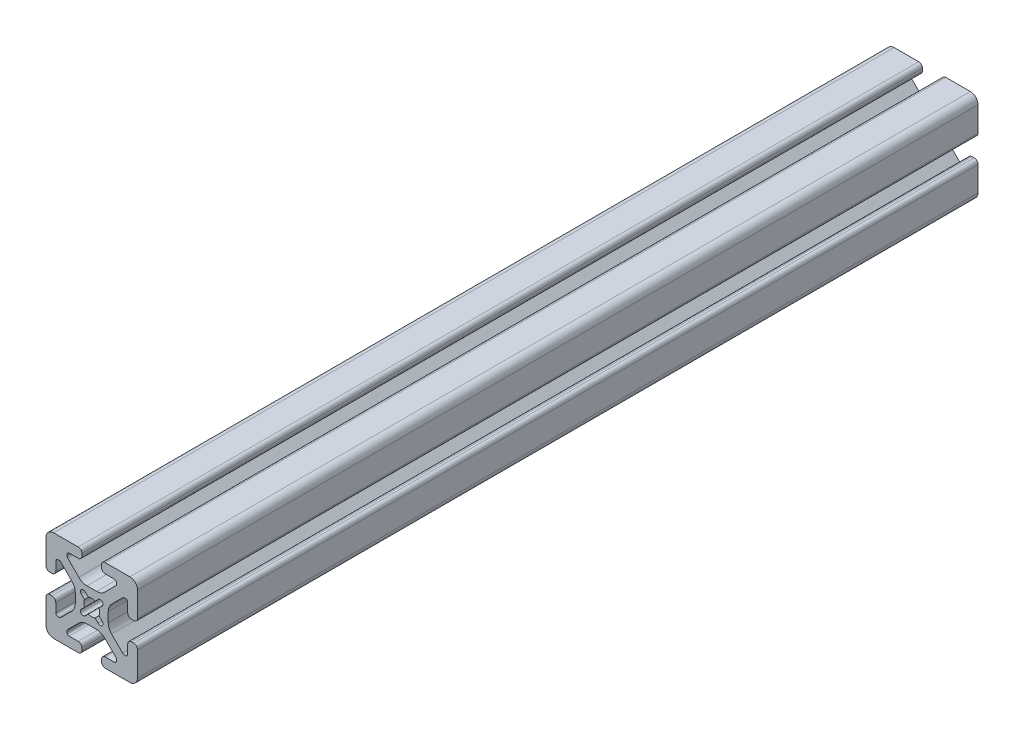
SolidWorks part; units mm, degrees
material "6061-T6 (SS)"
ref_plane "Front Plane" through (0, 0, 0) normal (0, 0, 1) x (1, 0, 0)
ref_plane "Top Plane" through (0, 0, 0) normal (0, 1, 0) x (1, 0, 0)
ref_plane "Right Plane" through (0, 0, 0) normal (1, 0, 0) x (0, 0, -1)
sketch "Sketch1" plane through (0, 0, 0) normal (0, 0, 1) x (1, 0, 0)
  line L0 (4.2456, 2.6398) -> (3.0178, 1.4017)
  line L1 (3.0179, -1.4014) -> (4.3433, -2.7269)
  line L2 (2.7269, -4.3433) -> (1.4014, -3.0179)
  line L3 (-1.4014, -3.0179) -> (-2.7269, -4.3433)
  line L4 (-4.3433, -2.7269) -> (-3.0179, -1.4014)
  line L5 (-3.0179, 1.4014) -> (-4.3433, 2.7269)
  line L6 (-2.7269, 4.3433) -> (-1.4014, 3.0179)
  line L7 (1.4017, 3.0178) -> (2.6398, 4.2456)
  line L8 (14.986, -5.6388) -> (14.986, -9.398)
  line L9 (14.097, -10.287) -> (13.5289, -10.287)
  line L10 (12.9003, -10.0266) -> (8.2608, -5.3872)
  line L11 (6.8697, -2.0285) -> (6.8697, 2.0285)
  line L12 (8.2608, 5.3872) -> (12.9003, 10.0266)
  line L13 (13.5289, 10.287) -> (14.097, 10.287)
  line L14 (14.986, 9.398) -> (14.986, 5.6388)
  line L15 (16.5608, 4.064) -> (17.4752, 4.064)
  line L16 (19.05, 5.6388) -> (19.05, 15.875)
  line L17 (15.875, 19.05) -> (5.6388, 19.05)
  line L18 (4.064, 17.4752) -> (4.064, 16.5608)
  line L19 (5.6388, 14.986) -> (9.398, 14.986)
  line L20 (10.287, 14.097) -> (10.287, 13.5289)
  line L21 (10.0266, 12.9003) -> (5.3872, 8.2608)
  line L22 (2.0285, 6.8697) -> (-2.0285, 6.8697)
  line L23 (-5.3872, 8.2608) -> (-10.0266, 12.9003)
  line L24 (-10.287, 13.5289) -> (-10.287, 14.097)
  line L25 (-9.398, 14.986) -> (-5.6388, 14.986)
  line L26 (-4.064, 16.5608) -> (-4.064, 17.4752)
  line L27 (-5.6388, 19.05) -> (-15.875, 19.05)
  line L28 (-19.05, 15.875) -> (-19.05, 5.6388)
  line L29 (-17.4752, 4.064) -> (-16.5608, 4.064)
  line L30 (-14.986, 5.6388) -> (-14.986, 9.398)
  line L31 (-14.097, 10.287) -> (-13.5289, 10.287)
  line L32 (-12.9003, 10.0266) -> (-8.2608, 5.3872)
  line L33 (-6.8697, 2.0285) -> (-6.8697, -2.0285)
  line L34 (-8.2608, -5.3872) -> (-12.9003, -10.0266)
  line L35 (-13.5289, -10.287) -> (-14.097, -10.287)
  line L36 (-14.986, -9.398) -> (-14.986, -5.6388)
  line L37 (-16.5608, -4.064) -> (-17.4752, -4.064)
  line L38 (-19.05, -5.6388) -> (-19.05, -15.875)
  line L39 (-15.875, -19.05) -> (-5.6388, -19.05)
  line L40 (-4.064, -17.4752) -> (-4.064, -16.5608)
  line L41 (-5.6388, -14.986) -> (-9.398, -14.986)
  line L42 (-10.287, -14.097) -> (-10.287, -13.5289)
  line L43 (-10.0266, -12.9003) -> (-5.3872, -8.2608)
  line L44 (-2.0285, -6.8697) -> (2.0285, -6.8697)
  line L45 (5.3872, -8.2608) -> (10.0266, -12.9003)
  line L46 (10.287, -13.5289) -> (10.287, -14.097)
  line L47 (9.398, -14.986) -> (5.6388, -14.986)
  line L48 (4.064, -16.5608) -> (4.064, -17.4752)
  line L49 (5.6388, -19.05) -> (15.875, -19.05)
  line L50 (19.05, -15.875) -> (19.05, -5.6388)
  line L51 (17.4752, -4.064) -> (16.5608, -4.064)
  arc A0 (4.2456, 2.6398) -> (2.6398, 4.2456) centre (3.5351, 3.5351) ccw
  arc A1 (1.4017, 3.0178) -> (-1.4014, 3.0179) centre (0, 0) ccw
  arc A2 (2.7269, -4.3433) -> (4.3433, -2.7269) centre (3.5351, -3.5351) ccw
  arc A3 (-3.0179, 1.4014) -> (-3.0179, -1.4014) centre (0, 0) ccw
  arc A4 (-4.3433, -2.7269) -> (-2.7269, -4.3433) centre (-3.5351, -3.5351) ccw
  arc A5 (-1.4014, -3.0179) -> (1.4014, -3.0179) centre (0, 0) ccw
  arc A6 (-2.7269, 4.3433) -> (-4.3433, 2.7269) centre (-3.5351, 3.5351) ccw
  arc A8 (16.5608, -4.064) -> (14.986, -5.6388) centre (16.5608, -5.6388) ccw
  arc A9 (14.097, -10.287) -> (14.986, -9.398) centre (14.097, -9.398) ccw
  arc A10 (12.9003, -10.0266) -> (13.5289, -10.287) centre (13.5289, -9.398) ccw
  arc A11 (6.8697, -2.0285) -> (8.2608, -5.3872) centre (11.6195, -2.0285) ccw
  arc A12 (8.2608, 5.3872) -> (6.8697, 2.0285) centre (11.6195, 2.0285) ccw
  arc A13 (13.5289, 10.287) -> (12.9003, 10.0266) centre (13.5289, 9.398) ccw
  arc A14 (14.986, 9.398) -> (14.097, 10.287) centre (14.097, 9.398) ccw
  arc A15 (14.986, 5.6388) -> (16.5608, 4.064) centre (16.5608, 5.6388) ccw
  arc A16 (17.4752, 4.064) -> (19.05, 5.6388) centre (17.4752, 5.6388) ccw
  arc A17 (19.05, 15.875) -> (15.875, 19.05) centre (15.875, 15.875) ccw
  arc A18 (5.6388, 19.05) -> (4.064, 17.4752) centre (5.6388, 17.4752) ccw
  arc A19 (4.064, 16.5608) -> (5.6388, 14.986) centre (5.6388, 16.5608) ccw
  arc A20 (10.287, 14.097) -> (9.398, 14.986) centre (9.398, 14.097) ccw
  arc A21 (10.0266, 12.9003) -> (10.287, 13.5289) centre (9.398, 13.5289) ccw
  arc A22 (2.0285, 6.8697) -> (5.3872, 8.2608) centre (2.0285, 11.6195) ccw
  arc A23 (-5.3872, 8.2608) -> (-2.0285, 6.8697) centre (-2.0285, 11.6195) ccw
  arc A24 (-10.287, 13.5289) -> (-10.0266, 12.9003) centre (-9.398, 13.5289) ccw
  arc A25 (-9.398, 14.986) -> (-10.287, 14.097) centre (-9.398, 14.097) ccw
  arc A26 (-5.6388, 14.986) -> (-4.064, 16.5608) centre (-5.6388, 16.5608) ccw
  arc A27 (-4.064, 17.4752) -> (-5.6388, 19.05) centre (-5.6388, 17.4752) ccw
  arc A28 (-15.875, 19.05) -> (-19.05, 15.875) centre (-15.875, 15.875) ccw
  arc A29 (-19.05, 5.6388) -> (-17.4752, 4.064) centre (-17.4752, 5.6388) ccw
  arc A30 (-16.5608, 4.064) -> (-14.986, 5.6388) centre (-16.5608, 5.6388) ccw
  arc A31 (-14.097, 10.287) -> (-14.986, 9.398) centre (-14.097, 9.398) ccw
  arc A32 (-12.9003, 10.0266) -> (-13.5289, 10.287) centre (-13.5289, 9.398) ccw
  arc A33 (-6.8697, 2.0285) -> (-8.2608, 5.3872) centre (-11.6195, 2.0285) ccw
  arc A34 (-8.2608, -5.3872) -> (-6.8697, -2.0285) centre (-11.6195, -2.0285) ccw
  arc A35 (-13.5289, -10.287) -> (-12.9003, -10.0266) centre (-13.5289, -9.398) ccw
  arc A36 (-14.986, -9.398) -> (-14.097, -10.287) centre (-14.097, -9.398) ccw
  arc A37 (-14.986, -5.6388) -> (-16.5608, -4.064) centre (-16.5608, -5.6388) ccw
  arc A38 (-17.4752, -4.064) -> (-19.05, -5.6388) centre (-17.4752, -5.6388) ccw
  arc A39 (-19.05, -15.875) -> (-15.875, -19.05) centre (-15.875, -15.875) ccw
  arc A40 (-5.6388, -19.05) -> (-4.064, -17.4752) centre (-5.6388, -17.4752) ccw
  arc A41 (-4.064, -16.5608) -> (-5.6388, -14.986) centre (-5.6388, -16.5608) ccw
  arc A42 (-10.287, -14.097) -> (-9.398, -14.986) centre (-9.398, -14.097) ccw
  arc A43 (-10.0266, -12.9003) -> (-10.287, -13.5289) centre (-9.398, -13.5289) ccw
  arc A44 (-2.0285, -6.8697) -> (-5.3872, -8.2608) centre (-2.0285, -11.6195) ccw
  arc A45 (5.3872, -8.2608) -> (2.0285, -6.8697) centre (2.0285, -11.6195) ccw
  arc A46 (10.287, -13.5289) -> (10.0266, -12.9003) centre (9.398, -13.5289) ccw
  arc A47 (9.398, -14.986) -> (10.287, -14.097) centre (9.398, -14.097) ccw
  arc A48 (5.6388, -14.986) -> (4.064, -16.5608) centre (5.6388, -16.5608) ccw
  arc A49 (4.064, -17.4752) -> (5.6388, -19.05) centre (5.6388, -17.4752) ccw
  arc A50 (15.875, -19.05) -> (19.05, -15.875) centre (15.875, -15.875) ccw
  arc A51 (19.05, -5.6388) -> (17.4752, -4.064) centre (17.4752, -5.6388) ccw
  arc A52 (3.0179, -1.4014) -> (3.0178, 1.4017) centre (0, 0) ccw
  dimension "D1" = 6.6548
extrude "Extrude1" add sketch "Sketch1" against normal blind 350
ref_plane "Plane1" through (0, 0, 0) normal (0, 1, 0) x (1, 0, 0)
ref_plane "Plane2" through (0, 0, 0) normal (-1, 0, 0) x (0, 0, 1)
ref_plane "Plane3" through (0, 0, 0) normal (0, 1, 0) x (1, 0, 0)
ref_plane "Plane4" through (0, 0, 0) normal (1, 0, 0) x (0, 0, -1)
